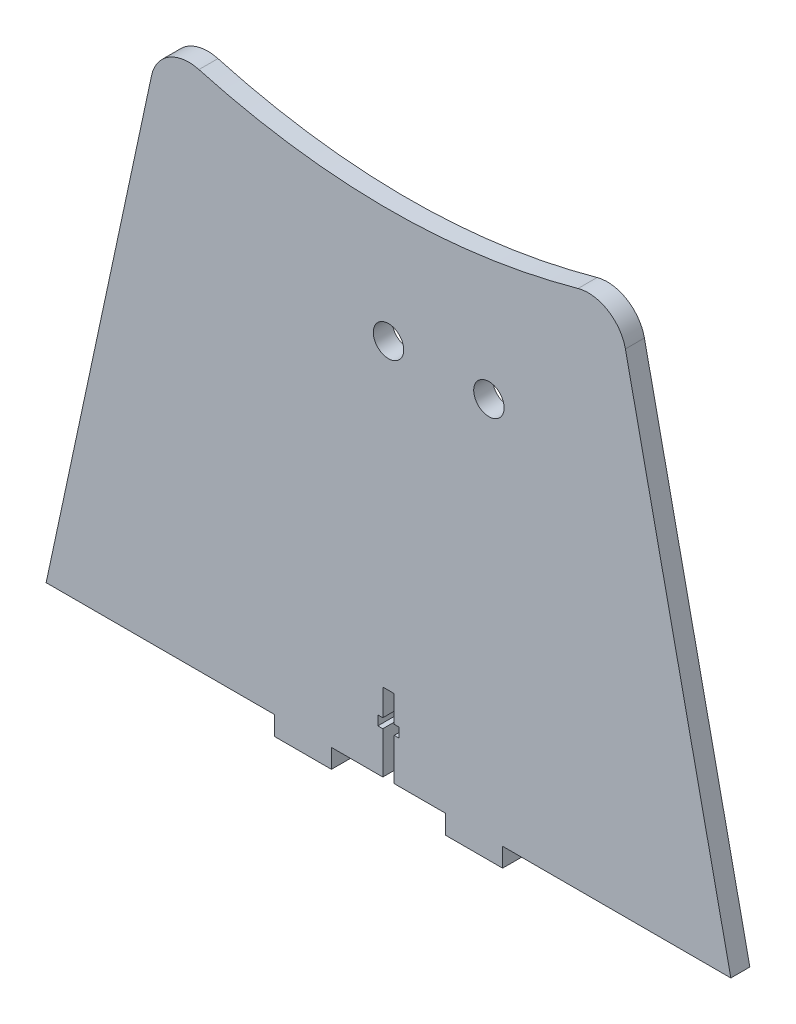
SolidWorks part; units mm, degrees
ref_plane "Front" through (0, 0, 0) normal (0, 0, 1) x (1, 0, 0)
ref_plane "Top" through (0, 0, 0) normal (0, 1, 0) x (1, 0, 0)
ref_plane "Right" through (0, 0, 0) normal (1, 0, 0) x (0, 0, -1)
sketch "Sketch1" plane through (0, 0, 0) normal (0, 0, 1) x (1, 0, 0)
  line L0 (-29.957, -40.1403) -> (-29.957, -45.1403)
  line L1 (-29.957, -45.1403) -> (-14.957, -45.1403)
  line L2 (-14.957, -45.1403) -> (-14.957, -40.1403)
  line L3 (15.043, -40.1403) -> (1.543, -40.1403)
  line L4 (15.043, -40.1403) -> (15.043, -45.1403)
  line L5 (15.043, -45.1403) -> (30.043, -45.1403)
  line L6 (30.043, -45.1403) -> (30.043, -40.1403)
  line L7 (90.043, -40.1403) -> (90.043, 59.8597) construction
  line L8 (-89.957, -40.1403) -> (-89.957, 59.8597) construction
  line L9 (-7.457, 70.1097) -> (33.943, 70.1097) construction
  line L10 (-7.457, 70.1097) -> (-7.457, 49.6097) construction
  line L11 (-7.457, 49.6097) -> (33.943, 49.6097) construction
  line L12 (33.943, 70.1097) -> (33.943, 49.6097) construction
  line L13 (33.943, 59.8597) -> (26.443, 59.8597) construction
  line L14 (-7.457, 59.8597) -> (0.043, 59.8597) construction
  line L15 (90.043, 59.8597) -> (-89.957, 59.8597) construction
  line L16 (60.043, -40.1403) -> (60.043, 99.8597) construction
  line L17 (-59.957, -40.1403) -> (-59.957, 99.8597) construction
  line L18 (90.043, -40.1403) -> (62.3238, 89.2161)
  line L19 (-89.957, -40.1403) -> (-62.2378, 89.2161)
  line L20 (0.043, -40.1403) -> (0.043, 89.8597) construction
  line L21 (-89.957, -40.1403) -> (-29.957, -40.1403)
  line L22 (30.043, -40.1403) -> (90.043, -40.1403)
  line L23 (-1.457, -19.6403) -> (1.543, -19.6403)
  line L24 (1.543, -29.1403) -> (2.843, -29.1403)
  line L25 (1.543, -26.6403) -> (1.543, -19.6403)
  line L26 (-1.457, -29.1403) -> (-2.757, -29.1403)
  line L27 (-1.457, -19.6403) -> (-1.457, -26.6403)
  line L28 (1.543, -40.1403) -> (1.543, -29.1403)
  line L29 (-1.457, -40.1403) -> (-1.457, -29.1403)
  line L30 (2.843, -29.1403) -> (2.843, -26.6403)
  line L31 (2.843, -26.6403) -> (1.543, -26.6403)
  line L32 (-1.457, -26.6403) -> (-2.757, -26.6403)
  line L33 (-2.757, -26.6403) -> (-2.757, -29.1403)
  line L34 (-1.457, -40.1403) -> (-14.957, -40.1403)
  circle A0 centre (-11.557, 65.0596) radius 1.6 construction
  circle A1 centre (-11.557, 54.6596) radius 1.6 construction
  circle A2 centre (38.043, 54.6596) radius 1.6 construction
  circle A3 centre (38.043, 65.0596) radius 1.6 construction
  arc A4 (-62.2378, 89.2161) -> (-49.7915, 96.7583) centre (-52.4598, 87.1208) cw
  arc A5 (62.3238, 89.2161) -> (49.8775, 96.7583) centre (52.5457, 87.1208) ccw
  circle A6 centre (26.443, 59.8597) radius 4
  circle A7 centre (0.043, 59.8597) radius 4
  spline S0 degree 3 poles (49.8775, 96.7583) (33.266, 92.1592) (0.043, 87.5602) (-33.18, 92.1592) (-49.7915, 96.7583) knots 0.084712 0.084712 0.084712 0.084712 0.5 0.915288 0.915288 0.915288 0.915288
  dimension "D1" = 10
extrude "Boss-Extrude1" add sketch "Sketch1" along normal blind 5
